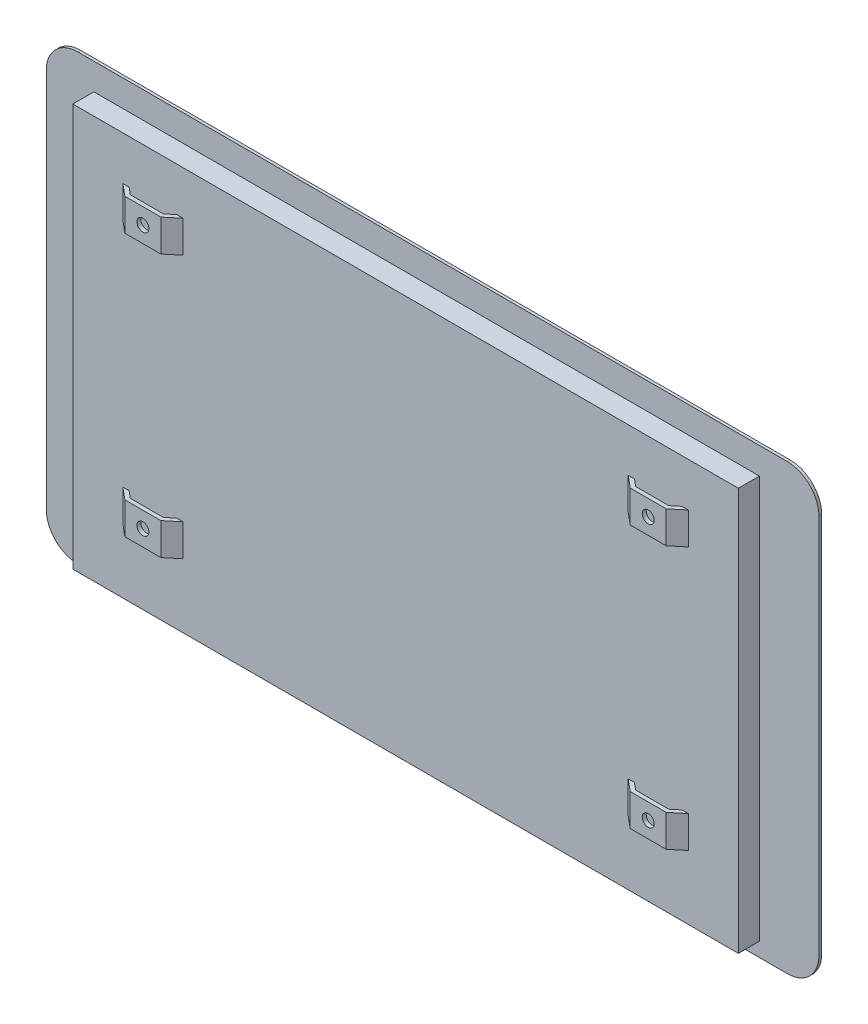
SolidWorks part; units mm, degrees
ref_plane "Front Plane" through (0, 0, 0) normal (0, 0, 1) x (1, 0, 0)
ref_plane "Top Plane" through (0, 0, 0) normal (0, 1, 0) x (1, 0, 0)
ref_plane "Right Plane" through (0, 0, 0) normal (1, 0, 0) x (0, 0, -1)
sketch "Sketch1" plane through (0, 0, 0) normal (0, 0, 1) x (1, 0, 0)
  line L0 (-88.6, 55.38) -> (88.6, 55.38)
  line L1 (-96.48, -55.38) -> (96.48, -55.38) construction
  line L2 (-96.48, -55.38) -> (-96.48, 55.38) construction
  line L3 (-96.48, 55.38) -> (96.48, 55.38) construction
  line L4 (96.48, -55.38) -> (96.48, 55.38) construction
  line L5 (-96.48, -55.38) -> (96.48, 55.38) construction
  line L6 (-96.48, 55.38) -> (96.48, -55.38) construction
  line L7 (-96.48, 47.5) -> (-96.48, -47.5)
  line L8 (-88.6, -55.38) -> (88.6, -55.38)
  line L9 (96.48, -47.5) -> (96.48, 47.5)
  arc A0 (-96.48, 47.5) -> (-88.6, 55.38) centre (-88.6, 47.5) cw
  arc A1 (88.6, 55.38) -> (96.48, 47.5) centre (88.6, 47.5) cw
  arc A2 (96.48, -47.5) -> (88.6, -55.38) centre (88.6, -47.5) cw
  arc A3 (-88.6, -55.38) -> (-96.48, -47.5) centre (-88.6, -47.5) cw
  circle A4 centre (0, 0) radius 1.5 construction
  point P0 (0, 0)
  dimension "D3" = 7.88
  dimension "D4" = 3
  dimension "D1" = 192.96
  dimension "D2" = 110.76
extrude "Boss-Extrude1" add sketch "Sketch1" along normal blind 0.7
sketch "Sketch2" plane through (0, 0, 0.7) normal (0, 0, 1) x (1, 0, 0)
  line L0 (88.6, 55.38) -> (-88.6, 55.38) construction
  line L1 (-84.59, 48.75) -> (81.61, 48.75)
  line L2 (-84.59, 48.75) -> (-84.59, -51.85)
  line L3 (-84.59, -51.85) -> (81.61, -51.85)
  line L4 (81.61, 48.75) -> (81.61, -51.85)
  line L5 (-84.59, 48.75) -> (81.61, -51.85) construction
  line L6 (-84.59, -51.85) -> (81.61, 48.75) construction
  line L7 (-96.48, 47.5) -> (-96.48, -47.5) construction
  point P4 (-1.49, -1.55)
  dimension "D1" = 6.63
  dimension "D2" = 11.89
  dimension "D3" = 100.6
  dimension "D4" = 166.2
extrude "Boss-Extrude2" add sketch "Sketch2" along normal blind 5.26
sketch "Sketch3" plane through (0, 0, 5.96) normal (0, 0, 1) x (1, 0, 0)
  line L0 (-84.59, 48.75) -> (-84.59, -51.85) construction
  line L1 (-72.09, 37.8) -> (-57.09, 37.8)
  line L2 (-72.09, 37.8) -> (-72.09, 29.8)
  line L3 (-72.09, 29.8) -> (-57.09, 29.8)
  line L4 (-57.09, 37.8) -> (-57.09, 29.8)
  line L5 (-72.09, 37.8) -> (-57.09, 29.8) construction
  line L6 (-72.09, 29.8) -> (-57.09, 37.8) construction
  line L7 (-72.09, -27.85) -> (-57.09, -27.85)
  line L8 (-72.09, -27.85) -> (-72.09, -35.85)
  line L9 (-72.09, -35.85) -> (-57.09, -35.85)
  line L10 (-57.09, -27.85) -> (-57.09, -35.85)
  line L11 (-72.09, -27.85) -> (-57.09, -35.85) construction
  line L12 (-72.09, -35.85) -> (-57.09, -27.85) construction
  line L13 (54.11, 37.8) -> (69.11, 37.8)
  line L14 (54.11, 37.8) -> (54.11, 29.8)
  line L15 (54.11, 29.8) -> (69.11, 29.8)
  line L16 (69.11, 37.8) -> (69.11, 29.8)
  line L17 (54.11, 37.8) -> (69.11, 29.8) construction
  line L18 (54.11, 29.8) -> (69.11, 37.8) construction
  line L19 (54.11, -27.85) -> (69.11, -27.85)
  line L20 (54.11, -27.85) -> (54.11, -35.85)
  line L21 (54.11, -35.85) -> (69.11, -35.85)
  line L22 (69.11, -27.85) -> (69.11, -35.85)
  line L23 (54.11, -27.85) -> (69.11, -35.85) construction
  line L24 (54.11, -35.85) -> (69.11, -27.85) construction
  line L27 (88.6, 55.38) -> (-88.6, 55.38) construction
  point P0 (-64.59, 33.8)
  point P5 (-64.59, -31.85)
  point P10 (61.61, 33.8)
  point P15 (61.61, -31.85)
  dimension "D1" = 20
  dimension "D2" = 21.58
  dimension "D3" = 65.65
  dimension "D4" = 126.2
  dimension "D5" = 15
  dimension "D6" = 8
extrude "Boss-Extrude3" add sketch "Sketch3" along normal blind 2.5
sketch "Sketch4" plane through (0, -35.85, 0) normal (0, -1, 0) x (1, 0, 0)
  line L0 (-72.09, 8.46) -> (-72.09, 5.96)
  line L1 (-72.09, 8.46) -> (-72.09, 5.96) construction
  line L2 (-72.09, 5.96) -> (-69.09, 8.46)
  line L3 (-72.09, 8.46) -> (-57.09, 8.46) construction
  line L4 (-69.09, 8.46) -> (-72.09, 8.46)
  line L5 (-57.09, 5.96) -> (-57.09, 8.46)
  line L6 (-57.09, 8.46) -> (-57.09, 5.96) construction
  line L7 (-57.09, 8.46) -> (-60.09, 8.46)
  line L8 (-60.09, 8.46) -> (-57.09, 5.96)
  line L9 (-60.452, 7.46) -> (-68.728, 7.46)
  line L10 (-84.59, 5.96) -> (81.61, 5.96) construction
  line L11 (-72.09, 5.96) -> (-57.09, 5.96) construction
  line L12 (-68.728, 7.46) -> (-70.528, 5.96)
  line L13 (-70.528, 5.96) -> (-58.652, 5.96)
  line L14 (-58.652, 5.96) -> (-60.452, 7.46)
  line L15 (-64.59, 8.46) -> (-64.59, 7.46) construction
  line L16 (-69.628, 6.71) -> (-70.2681, 7.4782) construction
  line L17 (-59.552, 6.71) -> (-58.9119, 7.4782) construction
  line L18 (-57.09, 8.46) -> (54.11, 8.46) construction
  line L19 (-1.49, 8.46) -> (-1.49, 5.96) construction
  line L20 (56.572, 6.71) -> (55.9319, 7.4782) construction
  line L21 (66.648, 6.71) -> (67.2881, 7.4782) construction
  line L22 (61.61, 8.46) -> (61.61, 7.46) construction
  line L23 (55.672, 5.96) -> (57.472, 7.46)
  line L24 (67.548, 5.96) -> (55.672, 5.96)
  line L25 (65.748, 7.46) -> (67.548, 5.96)
  line L26 (57.472, 7.46) -> (65.748, 7.46)
  line L27 (57.11, 8.46) -> (54.11, 5.96)
  line L28 (54.11, 8.46) -> (57.11, 8.46)
  line L29 (54.11, 5.96) -> (54.11, 8.46)
  line L30 (66.11, 8.46) -> (69.11, 8.46)
  line L31 (69.11, 5.96) -> (66.11, 8.46)
  line L32 (69.11, 8.46) -> (69.11, 5.96)
  point P16 (-64.59, 7.46)
  point P22 (-64.59, 8.46)
  dimension "D1" = 3
  dimension "D2" = 1
extrude "Cut-Extrude1" cut sketch "Sketch4" against normal through all both and the other way through all
sketch "Sketch5" plane through (0, 0, 8.46) normal (0, 0, 1) x (1, 0, 0)
  circle A0 centre (-64.59, 33.8) radius 1.5
  circle A1 centre (-64.59, -31.85) radius 1.5
  circle A2 centre (61.61, -31.85) radius 1.5
  circle A3 centre (61.61, 33.8) radius 1.5
  dimension "D1" = 3
extrude "Cut-Extrude2" cut sketch "Sketch5" against normal up to next
sketch "Sketch6" plane through (0, 0, 5.96) normal (0, 0, 1) x (1, 0, 0)
  line L0 (-21.314, 31.8946) -> (21.314, 31.8946) construction
  text T0 "Top"
  point P2 (0, 31.8946)
